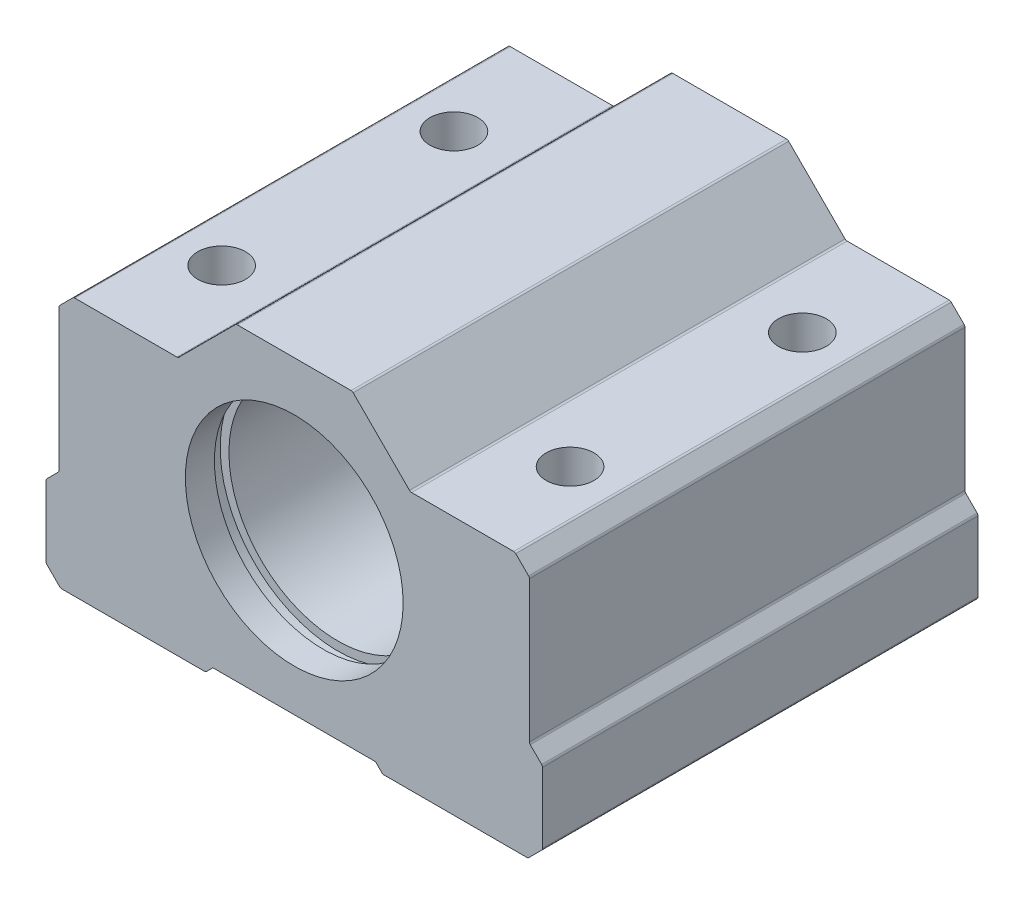
SolidWorks part; units mm, degrees
material "Alliage 2018"
ref_plane "Face" through (0, 0, 0) normal (0, 0, 1) x (1, 0, 0)
ref_plane "Dessus" through (0, 0, 0) normal (0, 1, 0) x (1, 0, 0)
ref_plane "Droite" through (0, 0, 0) normal (1, 0, 0) x (0, 0, -1)
sketch "Esquisse1" plane through (0, 0, 0) normal (0, 0, 1) x (1, 0, 0)
  line L0 (0, 0) -> (0, 21.8) construction
  line L1 (5.6, 0.5) -> (-5.6, 0.5)
  line L2 (-5.6, 0.5) -> (-6.1, 0)
  line L3 (-6.1, 0) -> (-17.1, 0)
  line L4 (-17.1, 0) -> (-17.1, 6)
  line L5 (-17.1, 6) -> (-16.2, 6.9)
  line L6 (-16.2, 6.9) -> (-16.2, 17.8)
  line L7 (-16.2, 17.8) -> (-8, 17.8)
  line L8 (-8, 17.8) -> (-4, 21.8)
  line L9 (-4, 21.8) -> (4, 21.8)
  line L10 (5.6, 0.5) -> (6.1, 0)
  line L11 (6.1, 0) -> (17.1, 0)
  line L12 (17.1, 0) -> (17.1, 6)
  line L13 (17.1, 6) -> (16.2, 6.9)
  line L14 (16.2, 6.9) -> (16.2, 17.8)
  line L15 (16.2, 17.8) -> (8, 17.8)
  line L16 (8, 17.8) -> (4, 21.8)
  circle A0 centre (0, 10.9) radius 7.5
  point P14 (0, 0.5)
  point P21 (0, 21.8)
  dimension "D10" = 15
  dimension "D1" = 34.2
  dimension "D2" = 32.4
  dimension "D3" = 16
  dimension "D4" = 11
  dimension "D5" = 45
  dimension "D6" = 0.5
  dimension "D7" = 6
  dimension "D8" = 17.8
  dimension "D9" = 21.8
extrude "Boss.-Extru.1" add sketch "Esquisse1" along normal mid plane 30
chamfer "Chanfrein1" distance 1 angle 45 4 edges at (-16.2, 17.8, 0) (16.2, 17.8, 0) (17.1, 0, 0) (-17.1, 0, 0)
fillet "Congé1" radius 0.2 20 edges at (6.1, 0, 0) (5.6, 0.5, 0) (-5.6, 0.5, 0) (-6.1, 0, 0) (-17.1, 6, 0) (-16.2, 6.9, 0) (-16.2, 16.8, 0) (17.1, 6, 0) (16.2, 6.9, 0) (16.2, 16.8, 0) (15.2, 17.8, 0) (8, 17.8, 0) (4, 21.8, 0) (-4, 21.8, 0) (-8, 17.8, 0) (-15.2, 17.8, 0) (17.1, 1, 0) (16.1, 0, 0) (-16.1, 0, 0) (-17.1, 1, 0)
ref_plane "Plan1" through (0, 0, 13) normal (0, 0, 1) x (1, 0, 0)
sketch "Esquisse2" plane through (0, 0, 13) normal (0, 0, 1) x (1, 0, 0)
  circle A0 centre (0, 10.9) radius 8.1
  dimension "D1" = 16.2
extrude "Enlèv. mat.-Extru.1" cut sketch "Esquisse2" against normal blind 1
ref_plane "Plan2" through (0, 0, -13) normal (0, 0, -1) x (-1, 0, 0)
sketch "Esquisse3" plane through (0, 0, -13) normal (0, 0, -1) x (-1, 0, 0)
  circle A1 centre (0, 10.9) radius 8.1 construction
  circle A2 centre (0, 10.9) radius 8.1
extrude "Enlèv. mat.-Extru.2" cut sketch "Esquisse3" against normal blind 1
hole_wizard "Trou taraudé M41" positions "Esquisse5" profile "Esquisse4" tap size "M4" standard "Iso" end condition through all
sketch "Esquisse5" plane through (0, 0, 0) normal (0, -1, 0) x (-1, 0, 0)
  line L0 (0, 0) -> (0, -15.8448) construction
  line L1 (0, 0) -> (-19.4284, 0) construction
  point P0 (-12, -8)
  point P2 (12, -8)
  point P4 (12, 8)
  point P6 (-12, 8)
  dimension "D1" = 24
  dimension "D2" = 16
sketch "Esquisse4" plane through (12, 0, 8) normal (1, 0, 0) x (0, 0, -1)
  line L0 (0, 0) -> (0, 21.8)
  line L1 (0, 21.8) -> (1.65, 21.8)
  line L2 (1.65, 21.8) -> (1.65, 0)
  line L5 (1.65, 0) -> (0, 0)
  line L11 (0, -6.35) -> (0, 107.95) construction
  dimension "Diamètre du trou pour taraudage jusqu'au prochain" = 3.3
  dimension "Profondeur du trou pour taraudage jusqu'au prochain" = 21.8
cosmetic thread "Filetage de perçage1" parameters "D2"=4
cosmetic thread "Filetage de perçage2" parameters "D2"=4
cosmetic thread "Filetage de perçage3" parameters "D2"=4
cosmetic thread "Filetage de perçage4" parameters "D2"=4
